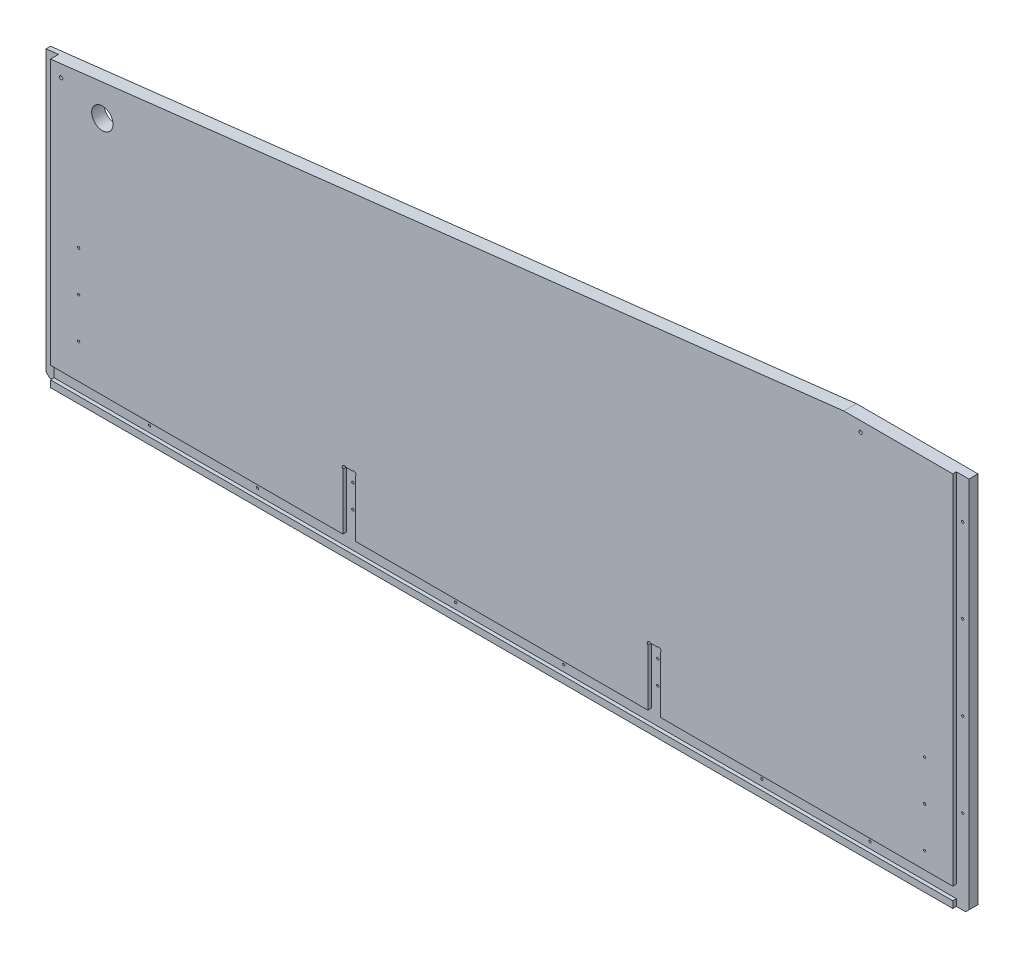
SolidWorks part; units mm, degrees
material "Pine"
ref_plane "Front Plane" through (0, 0, 0) normal (0, 0, 1) x (1, 0, 0)
ref_plane "Top Plane" through (0, 0, 0) normal (0, 1, 0) x (1, 0, 0)
ref_plane "Right Plane" through (0, 0, 0) normal (1, 0, 0) x (0, 0, -1)
sketch "Sketch1" plane through (0, 0, 0) normal (0, 0, 1) x (1, 0, 0)
  line L0 (8932.6508, -5243.5125) -> (10226.1458, -5243.5125)
  line L1 (9086.3208, -4722.0918) -> (10222.9708, -4853.7812)
  line L2 (8914.8708, -6342.0625) -> (10197.5708, -6342.0625)
  line L3 (8914.8708, -5808.6625) -> (10197.5708, -5808.6625)
  line L4 (8919.6333, -5253.0375) -> (10218.2083, -5253.0375)
  line L5 (9134.2633, -4656.1375) -> (9134.2633, -4638.3575)
  line L6 (9091.0833, -4638.3575) -> (9134.2633, -4638.3575)
  line L7 (9091.0833, -4567.2375) -> (9091.0833, -4638.3575)
  line L8 (9134.2633, -4656.1375) -> (9581.3033, -4656.1375)
  line L9 (9091.0833, -4567.2375) -> (9624.4833, -4567.2375)
  line L10 (9581.3033, -4656.1375) -> (9581.3033, -4638.3575)
  line L11 (9581.3033, -4638.3575) -> (9624.4833, -4638.3575)
  line L12 (9624.4833, -4567.2375) -> (9624.4833, -4638.3575)
  line L13 (8932.6508, -5225.7325) -> (9344.9775, -5225.7325)
  line L14 (8932.6508, -5256.2125) -> (8932.6508, -5243.5125)
  line L15 (8911.6958, -5256.2125) -> (8932.6508, -5256.2125)
  line L16 (8914.8708, -4722.0918) -> (9086.3208, -4722.0918)
  line L17 (8911.6958, -4715.5913) -> (8932.6508, -4715.5913)
  line L18 (8914.8708, -6342.0625) -> (8914.8708, -5808.6625)
  line L19 (12082.9917, -4722.0918) -> (10946.3417, -4853.7812)
  line L20 (12236.6617, -5243.5125) -> (10943.1667, -5243.5125)
  line L21 (10951.1042, -5253.0375) -> (12249.6792, -5253.0375)
  line L22 (10838.3917, -5656.2625) -> (11308.2917, -5656.2625)
  line L23 (10838.3917, -5719.7625) -> (11308.2917, -5719.7625)
  line L24 (10838.3917, -5742.5368) -> (11308.2917, -5742.5368)
  line L25 (10806.6417, -6342.0625) -> (11340.0417, -6342.0625)
  line L26 (10803.4667, -6335.7125) -> (11343.2167, -6335.7125)
  line L27 (10803.4667, -6317.9325) -> (11343.2167, -6317.9325)
  line L28 (10943.1667, -5225.7325) -> (11376.4483, -5225.7325)
  line L29 (11506.7292, -4754.5625) -> (10806.6417, -4827.5875)
  line L30 (11506.7292, -4567.2375) -> (11506.7292, -4754.5625)
  line L31 (10806.6417, -4567.2375) -> (10806.6417, -4827.5875)
  line L32 (10806.6417, -4567.2375) -> (11506.7292, -4567.2375)
  line L33 (10235.6708, -6329.3625) -> (10245.1958, -6329.3625)
  line L34 (10245.1958, -6329.3625) -> (10254.7208, -6278.5625)
  line L35 (10302.3458, -6329.3625) -> (10311.8708, -6278.5625)
  line L36 (10302.3458, -6329.3625) -> (10292.8208, -6329.3625)
  line L37 (10245.1958, -5821.3625) -> (10254.7208, -5872.1625)
  line L38 (10235.6708, -5821.3625) -> (10245.1958, -5821.3625)
  line L39 (10292.8208, -5821.3625) -> (10302.3458, -5821.3625)
  line L40 (10302.3458, -5821.3625) -> (10311.8708, -5872.1625)
  line L41 (10235.6708, -5821.3625) -> (10235.6708, -6329.3625)
  line L42 (10254.7208, -5872.1625) -> (10254.7208, -6278.5625)
  line L43 (10311.8708, -5872.1625) -> (10311.8708, -6278.5625)
  line L44 (10292.8208, -5821.3625) -> (10292.8208, -6329.3625)
  line L45 (8932.6508, -5225.7325) -> (8932.6508, -4715.5913)
  line L46 (8911.6958, -4715.5913) -> (8911.6958, -5256.2125)
  line L47 (8914.8708, -5248.275) -> (8914.8708, -4722.0918)
  line L48 (8919.6333, -5253.0375) -> (8914.8708, -5248.275)
  line L49 (8914.8708, -5145.0875) -> (8937.426, -5145.0875)
  line L50 (8914.8708, -5202.2375) -> (8937.426, -5202.2375)
  line L51 (10838.3917, -5656.2625) -> (10838.3917, -5719.7625)
  line L52 (10832.0417, -5736.1868) -> (10856.1717, -5736.1868)
  line L53 (10806.6417, -6342.0625) -> (10806.6417, -5818.7368)
  line L54 (10832.0417, -5649.9125) -> (10856.1717, -5649.9125)
  line L55 (10832.0417, -5726.1125) -> (10856.1717, -5726.1125)
  line L56 (10806.6417, -5818.7368) -> (10833.9015, -5818.7368)
  line L57 (10832.0417, -5806.0442) -> (10851.6815, -5806.0442)
  line L58 (10856.1717, -5801.5541) -> (10856.1717, -5736.1868)
  line L59 (10838.3917, -5814.2467) -> (10838.3917, -5742.5368)
  line L60 (10832.0417, -5806.0442) -> (10832.0417, -5736.1868)
  line L61 (10803.4667, -6317.9325) -> (10803.4667, -6335.7125)
  line L62 (10197.5708, -5808.6625) -> (10197.5708, -6342.0625)
  line L63 (9762.3842, -6348.4125) -> (9762.3842, -5802.3125)
  line L64 (9780.1642, -6348.4125) -> (9762.3842, -6348.4125)
  line L65 (9780.1642, -5802.3125) -> (9780.1642, -6348.4125)
  line L66 (9762.3842, -5802.3125) -> (9780.1642, -5802.3125)
  line L67 (9332.2775, -6348.4125) -> (9332.2775, -5802.3125)
  line L68 (9332.2775, -6348.4125) -> (9350.0575, -6348.4125)
  line L69 (9350.0575, -5802.3125) -> (9350.0575, -6348.4125)
  line L70 (9332.2775, -5802.3125) -> (9350.0575, -5802.3125)
  line L71 (9993.8374, -6061.075) -> (9993.8374, -6045.2418)
  line L72 (9998.5999, -6065.8375) -> (10014.4331, -6065.8375)
  line L73 (9998.5999, -6084.8875) -> (10014.4331, -6084.8875)
  line L74 (9993.8374, -6105.4832) -> (9993.8374, -6089.65)
  line L75 (9974.7874, -6105.4832) -> (9974.7874, -6089.65)
  line L76 (9954.1917, -6084.8875) -> (9970.0249, -6084.8875)
  line L77 (9974.7874, -6061.075) -> (9974.7874, -6045.2418)
  line L78 (9954.1917, -6065.8375) -> (9970.0249, -6065.8375)
  line L79 (10793.9417, -6237.2875) -> (10816.4969, -6237.2875)
  line L80 (10793.9417, -6294.4375) -> (10816.4969, -6294.4375)
  line L81 (10856.1717, -5649.9125) -> (10856.1717, -5726.1125)
  line L82 (10832.0417, -5726.1125) -> (10832.0417, -5649.9125)
  line L83 (10226.1458, -5225.7325) -> (10226.1458, -5243.5125)
  line L84 (10205.1908, -5257.8) -> (10205.1908, -4844.2499)
  line L85 (10230.9083, -4844.2499) -> (10230.9083, -5257.8)
  line L86 (10205.1908, -5257.8) -> (10230.9083, -5257.8)
  line L87 (10205.1908, -4844.2499) -> (10230.9083, -4844.2499)
  line L88 (10946.3417, -5176.8375) -> (10968.8969, -5176.8375)
  line L89 (9349.4676, -5141.9125) -> (9358.2674, -5141.9125)
  line L90 (10946.3417, -5119.6875) -> (10968.8969, -5119.6875)
  line L91 (9929.011, -4660.9635) -> (10066.0807, -4660.9635)
  line L92 (9929.011, -4678.7435) -> (10066.0807, -4678.7435)
  line L93 (10943.1667, -5225.7325) -> (10943.1667, -5243.5125)
  line L94 (10946.3417, -5248.275) -> (10951.1042, -5253.0375)
  line L95 (10946.3417, -5257.8063) -> (10946.3417, -4849.0188)
  line L96 (10964.1217, -5257.8) -> (10964.1217, -4844.2499)
  line L97 (10938.4042, -4844.2499) -> (10938.4042, -5257.8)
  line L98 (10938.4042, -5257.8) -> (10964.1217, -5257.8)
  line L99 (10964.1217, -4844.2499) -> (10938.4042, -4844.2499)
  line L100 (10344.8908, -4560.8875) -> (10369.0208, -4560.8875)
  line L101 (10344.8908, -4560.8875) -> (10369.0208, -4560.8875)
  line L102 (10800.2917, -4560.8875) -> (10824.4217, -4560.8875)
  line L103 (10200.4156, -5119.6875) -> (10222.9708, -5119.6875)
  line L104 (10200.4156, -5176.8375) -> (10222.9708, -5176.8375)
  line L105 (9344.9775, -5146.4026) -> (9344.9775, -5225.7325)
  line L106 (10344.8908, -4560.8875) -> (10344.8908, -4833.9375)
  line L107 (9792.8642, -5225.7325) -> (9792.8642, -5146.4026)
  line L108 (9362.7575, -5225.7325) -> (9775.0842, -5225.7325)
  line L109 (9680.3633, -4761.8396) -> (9680.3633, -4559.9604)
  line L110 (9656.2333, -4559.9604) -> (9680.3633, -4559.9604)
  line L111 (9656.2333, -4761.8396) -> (9680.3633, -4761.8396)
  line L112 (9656.2333, -4761.8396) -> (9656.2333, -4559.9604)
  line L113 (9779.5743, -5141.9125) -> (9788.374, -5141.9125)
  line L114 (10070.5708, -4665.4536) -> (10070.5708, -4674.2534)
  line L115 (9924.5208, -4674.2534) -> (9924.5208, -4665.4536)
  line L116 (12127.4417, -6188.3925) -> (12205.5015, -6188.3925)
  line L117 (12209.9917, -6170.6125) -> (12209.9917, -6183.9024)
  line L118 (9792.8642, -5225.7325) -> (10226.1458, -5225.7325)
  line L119 (9662.5833, -4754.5625) -> (10362.6708, -4827.5875)
  line L120 (9662.5833, -4567.2375) -> (9662.5833, -4754.5625)
  line L121 (10362.6708, -4567.2375) -> (10362.6708, -4827.5875)
  line L122 (9662.5833, -4567.2375) -> (10362.6708, -4567.2375)
  line L123 (10824.4217, -4833.9375) -> (10800.2917, -4833.9375)
  line L124 (10800.2917, -4833.9375) -> (10800.2917, -4560.8875)
  line L125 (10824.4217, -4560.8875) -> (10824.4217, -4833.9375)
  line L126 (10344.8908, -4833.9375) -> (10369.0208, -4833.9375)
  line L127 (10369.0208, -4833.9375) -> (10369.0208, -4560.8875)
  line L128 (10222.9708, -5248.275) -> (10218.2083, -5253.0375)
  line L129 (10222.9708, -5257.8063) -> (10222.9708, -4849.0188)
  line L130 (11734.6544, -5701.375) -> (11739.2301, -5701.375)
  line L131 (9362.7575, -5225.7325) -> (9362.7575, -5146.4026)
  line L132 (9775.0842, -5146.4026) -> (9775.0842, -5225.7325)
  line L133 (11761.3864, -5701.375) -> (11756.8282, -5701.375)
  line L134 (11734.6544, -5693.755) -> (11739.2301, -5693.755)
  line L135 (11761.4039, -5693.755) -> (11756.8282, -5693.755)
  line L136 (11734.6544, -5701.375) -> (11739.2301, -5701.375)
  line L137 (11744.3462, -5721.3024) -> (11744.3462, -5706.4179)
  line L138 (11751.7122, -5721.3024) -> (11751.7122, -5706.4179)
  line L139 (11740.0917, -6170.6125) -> (11740.0917, -6183.9024)
  line L140 (11689.2917, -6188.3925) -> (11822.6417, -6188.3925)
  line L141 (11689.2917, -6348.4093) -> (11689.2917, -6164.2657)
  line L142 (11689.2917, -6164.2657) -> (11746.4417, -6164.2657)
  line L143 (11746.4417, -6164.2657) -> (11746.4417, -6188.3925)
  line L144 (11689.2917, -6164.2657) -> (11746.4417, -6164.2657)
  line L145 (11340.0417, -5818.7368) -> (11340.0417, -6342.0625)
  line L146 (11290.5117, -5726.1125) -> (11314.6417, -5726.1125)
  line L147 (11290.5117, -5649.9125) -> (11290.5117, -5726.1125)
  line L148 (11340.0417, -5818.7368) -> (11312.7818, -5818.7368)
  line L149 (11314.6417, -5806.0442) -> (11295.0018, -5806.0442)
  line L150 (11290.5117, -5801.5541) -> (11290.5117, -5736.1868)
  line L151 (11308.2917, -5814.2467) -> (11308.2917, -5742.5368)
  line L152 (11314.6417, -5806.0442) -> (11314.6417, -5736.1868)
  line L153 (11290.5117, -5736.1868) -> (11314.6417, -5736.1868)
  line L154 (11848.0417, -6267.1325) -> (11962.3417, -6267.1325)
  line L155 (11962.3417, -6267.1325) -> (11962.3417, -6203.6325)
  line L156 (11343.2167, -6317.9325) -> (11343.2167, -6335.7125)
  line L157 (11365.4417, -5656.2625) -> (11365.4417, -5719.7625)
  line L158 (11365.4417, -5656.2625) -> (11479.7417, -5656.2625)
  line L159 (11778.1917, -6071.3937) -> (11802.3217, -6071.3937)
  line L160 (11314.6417, -5726.1125) -> (11314.6417, -5649.9125)
  line L161 (11314.6417, -5649.9125) -> (11290.5117, -5649.9125)
  line L162 (11308.2917, -5719.7625) -> (11308.2917, -5656.2625)
  line L163 (11689.2917, -6348.4093) -> (11713.4217, -6348.4093)
  line L164 (12203.6417, -6164.2657) -> (12260.7917, -6164.2657)
  line L165 (11713.4217, -6348.4093) -> (11713.4217, -6164.2657)
  line L166 (11695.6417, -6342.0625) -> (11695.6417, -6170.6125)
  line L167 (11695.6417, -6048.5337) -> (11699.4517, -6052.3437)
  line L168 (11822.6417, -6292.5325) -> (11822.6417, -6188.3925)
  line L169 (11695.6417, -6342.0625) -> (11695.6417, -6170.6125)
  line L170 (11848.0417, -6203.6325) -> (11962.3417, -6203.6325)
  line L171 (11848.0417, -6203.6325) -> (11848.0417, -6267.1325)
  line L172 (11987.7417, -6267.1325) -> (11987.7417, -6203.6325)
  line L173 (11784.5417, -6077.7437) -> (11784.5417, -6141.2438)
  line L174 (11517.8417, -5656.2625) -> (11632.1417, -5656.2625)
  line L175 (11632.1417, -5656.2625) -> (11632.1417, -5719.7625)
  line L176 (11632.1417, -5719.7625) -> (11517.8417, -5719.7625)
  line L177 (11517.8417, -5719.7625) -> (11517.8417, -5656.2625)
  line L178 (11692.4667, -6028.2137) -> (11692.4667, -6045.9937)
  line L179 (11695.6417, -5979.3188) -> (11718.1969, -5979.3188)
  line L180 (11695.6417, -5922.1687) -> (11718.1969, -5922.1687)
  line L181 (11821.0415, -5722.9375) -> (11821.0415, -5943.6)
  line L182 (11687.7042, -5651.5) -> (11701.9917, -5651.5)
  line L183 (11687.7042, -5651.5) -> (11687.7042, -6055.5251)
  line L184 (11687.7042, -6055.5251) -> (11701.9917, -6055.5251)
  line L185 (11701.9917, -6055.5251) -> (11701.9917, -5651.5)
  line L186 (11695.6417, -6055.2013) -> (11695.6417, -5649.595)
  line L187 (11695.6417, -5656.2625) -> (11695.6417, -6048.5337)
  line L188 (11695.6417, -6170.6125) -> (11740.0917, -6170.6125)
  line L189 (12203.6417, -6164.2657) -> (12203.6417, -6188.3925)
  line L190 (12254.4417, -6342.0625) -> (12254.4417, -6170.6125)
  line L191 (12129.0419, -5943.6) -> (12129.0419, -5722.9375)
  line L192 (12254.4417, -6048.5337) -> (12250.6317, -6052.3437)
  line L193 (12257.6167, -6045.9937) -> (12257.6167, -6028.2137)
  line L194 (12248.0917, -5651.5) -> (12262.3792, -5651.5)
  line L195 (12262.3792, -5651.5) -> (12262.3792, -6055.5251)
  line L196 (12262.3792, -6055.5251) -> (12248.0917, -6055.5251)
  line L197 (12248.0917, -6055.5251) -> (12248.0917, -5651.5)
  line L198 (12254.4417, -6141.2438) -> (12254.4417, -6077.7437)
  line L199 (12236.6617, -6164.2657) -> (12260.7917, -6164.2657)
  line L200 (12102.0417, -6267.1325) -> (11987.7417, -6267.1325)
  line L201 (11330.1865, -6237.2875) -> (11352.7417, -6237.2875)
  line L202 (11330.1865, -6294.4375) -> (11352.7417, -6294.4375)
  line L203 (11474.6617, -5851.8425) -> (11492.4417, -5851.8425)
  line L204 (11474.6617, -5808.6625) -> (11474.6617, -5851.8425)
  line L205 (11403.5417, -5808.6625) -> (11474.6617, -5808.6625)
  line L206 (11492.4417, -5851.8425) -> (11492.4417, -6298.8825)
  line L207 (11403.5417, -6342.0625) -> (11403.5417, -5808.6625)
  line L208 (11474.6617, -6298.8825) -> (11492.4417, -6298.8825)
  line L209 (11474.6617, -6342.0625) -> (11474.6617, -6298.8825)
  line L210 (11403.5417, -6342.0625) -> (11474.6617, -6342.0625)
  line L211 (11619.4417, -5851.8425) -> (11601.6617, -5851.8425)
  line L212 (11601.6617, -5808.6625) -> (11601.6617, -5851.8425)
  line L213 (11530.5417, -5808.6625) -> (11601.6617, -5808.6625)
  line L214 (11619.4417, -5851.8425) -> (11619.4417, -6298.8825)
  line L215 (11530.5417, -6342.0625) -> (11530.5417, -5808.6625)
  line L216 (11619.4417, -6298.8825) -> (11601.6617, -6298.8825)
  line L217 (11601.6617, -6342.0625) -> (11601.6617, -6298.8825)
  line L218 (11530.5417, -6342.0625) -> (11601.6617, -6342.0625)
  line L219 (11479.7417, -5719.7625) -> (11479.7417, -5656.2625)
  line L220 (11365.4417, -5719.7625) -> (11479.7417, -5719.7625)
  line L221 (11778.1917, -6147.5937) -> (11802.3217, -6147.5937)
  line L222 (11802.3217, -6071.3937) -> (11802.3217, -6147.5937)
  line L223 (11778.1917, -6147.5937) -> (11778.1917, -6071.3937)
  line L224 (12254.4417, -5922.1687) -> (12231.8865, -5922.1687)
  line L225 (12254.4417, -5979.3188) -> (12231.8865, -5979.3188)
  line L226 (12254.4417, -6055.2013) -> (12254.4417, -5649.595)
  line L227 (12254.4417, -6048.5337) -> (12254.4417, -5656.2625)
  line L228 (11841.6917, -5702.2873) -> (12108.3917, -5702.2873)
  line L229 (11822.6417, -6292.5325) -> (12127.4417, -6292.5325)
  line L230 (12127.4417, -6292.5325) -> (12127.4417, -6188.3925)
  line L231 (12254.4417, -6170.6125) -> (12209.9917, -6170.6125)
  line L232 (11695.6417, -6342.0625) -> (12254.4417, -6342.0625)
  line L233 (12236.6617, -6348.4093) -> (12260.7917, -6348.4093)
  line L234 (12260.7917, -6348.4093) -> (12260.7917, -6164.2657)
  line L235 (12236.6617, -6348.4093) -> (12236.6617, -6164.2657)
  line L236 (12102.0417, -6203.6325) -> (12102.0417, -6267.1325)
  line L237 (11987.7417, -6203.6325) -> (12102.0417, -6203.6325)
  line L238 (12236.6617, -6147.5937) -> (12236.6617, -6071.3937)
  line L239 (12203.6417, -6188.3925) -> (12260.7917, -6188.3925)
  line L240 (11098.7417, -4665.4536) -> (11098.7417, -4674.2534)
  line L241 (11394.2283, -5146.4026) -> (11394.2283, -5225.7325)
  line L242 (11376.4483, -5225.7325) -> (11376.4483, -5146.4026)
  line L243 (11394.2283, -5225.7325) -> (11806.555, -5225.7325)
  line L244 (11841.6917, -5964.2502) -> (12108.3917, -5964.2502)
  line L245 (12236.6617, -6147.5937) -> (12260.7917, -6147.5937)
  line L246 (12236.6617, -5256.2125) -> (12236.6617, -5243.5125)
  line L247 (12260.7917, -6147.5937) -> (12260.7917, -6071.3937)
  line L248 (12260.7917, -6071.3937) -> (12236.6617, -6071.3937)
  line L249 (12254.4417, -6077.7437) -> (11784.5417, -6077.7437)
  line L250 (11784.5417, -6141.2438) -> (12254.4417, -6141.2438)
  line L252 (12254.4417, -5656.2625) -> (11695.6417, -5656.2625)
  line L253 (11699.4517, -6052.3437) -> (12250.6317, -6052.3437)
  line L254 (11692.4667, -6045.9937) -> (12257.6167, -6045.9937)
  line L255 (11692.4667, -6028.2137) -> (12257.6167, -6028.2137)
  line L256 (11824.335, -5146.4026) -> (11824.335, -5225.7325)
  line L257 (11811.0451, -5141.9125) -> (11819.8449, -5141.9125)
  line L258 (11244.7917, -4674.2534) -> (11244.7917, -4665.4536)
  line L259 (11806.555, -5225.7325) -> (11806.555, -5146.4026)
  line L260 (11488.9492, -4761.8396) -> (11488.9492, -4559.9604)
  line L261 (11488.9492, -4559.9604) -> (11513.0792, -4559.9604)
  line L262 (11488.9492, -4761.8396) -> (11513.0792, -4761.8396)
  line L263 (11513.0792, -4761.8396) -> (11513.0792, -4559.9604)
  line L264 (11240.3015, -4660.9635) -> (11103.2318, -4660.9635)
  line L265 (11103.2318, -4678.7435) -> (11240.3015, -4678.7435)
  line L266 (12236.6617, -5225.7325) -> (12236.6617, -4715.5913)
  line L267 (12257.6167, -4715.5913) -> (12257.6167, -5256.2125)
  line L268 (12254.4417, -5248.275) -> (12254.4417, -4722.0918)
  line L269 (12236.6617, -5225.7325) -> (11824.335, -5225.7325)
  line L270 (12035.0492, -4656.1375) -> (12035.0492, -4638.3575)
  line L271 (12078.2292, -4638.3575) -> (12035.0492, -4638.3575)
  line L272 (12078.2292, -4567.2375) -> (12078.2292, -4638.3575)
  line L273 (12035.0492, -4656.1375) -> (11588.0092, -4656.1375)
  line L274 (11544.8292, -4567.2375) -> (12078.2292, -4567.2375)
  line L275 (11588.0092, -4656.1375) -> (11588.0092, -4638.3575)
  line L276 (11544.8292, -4638.3575) -> (11588.0092, -4638.3575)
  line L277 (11544.8292, -4567.2375) -> (11544.8292, -4638.3575)
  line L278 (12249.6792, -5253.0375) -> (12254.4417, -5248.275)
  line L280 (12257.6167, -5256.2125) -> (12236.6617, -5256.2125)
  line L281 (12231.8865, -5145.0875) -> (12254.4417, -5145.0875)
  line L282 (12231.8865, -5202.2375) -> (12254.4417, -5202.2375)
  line L283 (12236.6617, -4715.5913) -> (12257.6167, -4715.5913)
  line L284 (12082.9917, -4722.0918) -> (12254.4417, -4722.0918)
  line L285 (11380.9385, -5141.9125) -> (11389.7382, -5141.9125)
  circle A0 centre (8923.7608, -4778.9042) radius 1.5875
  circle A1 centre (9062.6598, -4736.3765) radius 2.3685
  circle A2 centre (9051.3958, -6281.7375) radius 22.225
  circle A3 centre (9083.1458, -6249.9875) radius 1.5875
  circle A4 centre (9083.1458, -6313.4875) radius 1.5875
  circle A5 centre (9019.6458, -6249.9875) radius 1.5875
  circle A6 centre (9019.6458, -6313.4875) radius 1.5875
  circle A7 centre (8972.3383, -5202.2375) radius 1.5875
  circle A8 centre (8923.7608, -5015.9708) radius 1.5875
  circle A9 centre (8923.7608, -5134.5042) radius 1.5875
  circle A10 centre (9054.5708, -5234.6225) radius 1.5875
  circle A11 centre (8923.7608, -4897.4375) radius 1.5875
  circle A12 centre (8972.3383, -5087.9375) radius 1.5875
  circle A13 centre (8972.3383, -5145.0875) radius 1.5875
  circle A14 centre (10847.2817, -5668.9625) radius 1.5875
  circle A15 centre (10847.2817, -5707.0625) radius 1.5875
  circle A16 centre (10847.2817, -5755.2368) radius 1.5875
  circle A17 centre (10851.4092, -6237.2875) radius 1.5875
  circle A18 centre (10851.4092, -6294.4375) radius 1.5875
  circle A19 centre (10847.2817, -5793.3442) radius 1.5875
  arc A20 (10833.9015, -5818.7368) -> (10838.3917, -5814.2467) centre (10836.1466, -5816.4918) ccw
  arc A21 (10851.6815, -5806.0442) -> (10856.1717, -5801.5541) centre (10853.9266, -5803.7992) ccw
  circle A22 centre (10882.8417, -6040.4375) radius 1.5875
  circle A23 centre (10882.8417, -6218.2375) radius 1.5875
  circle A24 centre (10882.8417, -5862.6375) radius 1.5875
  circle A25 centre (10908.2417, -6326.8225) radius 1.5875
  circle A26 centre (10908.2417, -6326.8225) radius 1.5875
  circle A27 centre (10851.4092, -6180.1375) radius 1.5875
  circle A28 centre (10815.5317, -4783.4231) radius 1.5875
  circle A29 centre (10815.5317, -4696.9488) radius 1.5875
  circle A30 centre (10815.5317, -4610.4746) radius 1.5875
  circle A31 centre (10979.1323, -4867.0082) radius 2.3685
  circle A32 centre (10190.1802, -4867.0082) radius 2.3685
  circle A33 centre (10955.2317, -4929.9812) radius 1.5875
  circle A34 centre (10955.2317, -5031.5812) radius 1.5875
  circle A35 centre (10214.0808, -4929.9812) radius 1.5875
  circle A36 centre (10214.0808, -5031.5812) radius 1.5875
  circle A37 centre (9341.1675, -6265.8625) radius 1.5875
  circle A38 centre (9771.2742, -5884.8625) radius 1.5875
  circle A39 centre (9771.2742, -6138.8625) radius 1.5875
  circle A40 centre (9771.2742, -6011.8625) radius 1.5875
  arc A41 (10036.2287, -6113.8083) -> (10051.3426, -6111.6033) centre (10042.9639, -6107.0732) ccw
  arc A42 (10051.3426, -6111.6033) -> (10051.3426, -6039.1217) centre (9984.3124, -6075.3625) ccw
  arc A43 (10051.3426, -6039.1217) -> (10036.2287, -6036.9167) centre (10042.9639, -6043.6518) ccw
  arc A44 (10034.5851, -6102.5431) -> (10034.5851, -6048.1819) centre (9984.3124, -6075.3625) ccw
  arc A45 (10034.5851, -6102.5431) -> (10036.2287, -6113.8083) centre (10042.9639, -6107.0732) ccw
  arc A46 (10036.2287, -6036.9167) -> (10034.5851, -6048.1819) centre (10042.9639, -6043.6518) ccw
  arc A47 (9945.8666, -6127.2787) -> (9948.0717, -6142.3927) centre (9952.6018, -6134.0139) ccw
  arc A48 (9948.0717, -6142.3927) -> (10020.5532, -6142.3927) centre (9984.3124, -6075.3625) ccw
  arc A49 (10020.5532, -6142.3927) -> (10022.7583, -6127.2787) centre (10016.0231, -6134.0139) ccw
  arc A50 (9957.1319, -6125.6352) -> (10011.493, -6125.6352) centre (9984.3124, -6075.3625) ccw
  arc A51 (9957.1319, -6125.6352) -> (9945.8666, -6127.2787) centre (9952.6018, -6134.0139) ccw
  arc A52 (10022.7583, -6127.2787) -> (10011.493, -6125.6352) centre (10016.0231, -6134.0139) ccw
  arc A53 (9932.3962, -6036.9167) -> (9917.2822, -6039.1217) centre (9925.661, -6043.6518) ccw
  arc A54 (9917.2822, -6039.1217) -> (9917.2822, -6111.6033) centre (9984.3124, -6075.3625) ccw
  arc A55 (9917.2822, -6111.6033) -> (9932.3962, -6113.8083) centre (9925.661, -6107.0732) ccw
  arc A56 (9934.0398, -6048.1819) -> (9934.0398, -6102.5431) centre (9984.3124, -6075.3625) ccw
  arc A57 (9934.0398, -6048.1819) -> (9932.3962, -6036.9167) centre (9925.661, -6043.6518) ccw
  arc A58 (9932.3962, -6113.8083) -> (9934.0398, -6102.5431) centre (9925.661, -6107.0732) ccw
  arc A59 (9945.8666, -6023.4463) -> (9957.1319, -6025.0898) centre (9952.6018, -6016.7111) ccw
  arc A60 (10011.493, -6025.0898) -> (10022.7583, -6023.4463) centre (10016.0231, -6016.7111) ccw
  arc A61 (10011.493, -6025.0898) -> (9957.1319, -6025.0898) centre (9984.3124, -6075.3625) ccw
  arc A62 (9948.0717, -6008.3323) -> (9945.8666, -6023.4463) centre (9952.6018, -6016.7111) ccw
  arc A63 (10020.5532, -6008.3323) -> (9948.0717, -6008.3323) centre (9984.3124, -6075.3625) ccw
  arc A64 (10022.7583, -6023.4463) -> (10020.5532, -6008.3323) centre (10016.0231, -6016.7111) ccw
  arc A65 (10005.0943, -6187.7574) -> (10096.7073, -6096.1443) centre (9984.3124, -6075.3625) ccw
  arc A66 (9993.8374, -6178.3911) -> (10005.0943, -6187.7574) centre (10003.3624, -6178.3911) ccw
  arc A67 (10001.6306, -6169.0249) -> (10077.9748, -6092.6807) centre (9984.3124, -6075.3625) ccw
  arc A68 (10087.3411, -6084.8875) -> (10077.9748, -6092.6807) centre (10087.3411, -6094.4125) ccw
  arc A69 (10001.6306, -6169.0249) -> (9993.8374, -6178.3911) centre (10003.3624, -6178.3911) ccw
  arc A70 (9963.5306, -6187.7574) -> (9974.7874, -6178.3911) centre (9965.2624, -6178.3911) ccw
  arc A71 (9871.9176, -6096.1443) -> (9963.5306, -6187.7574) centre (9984.3124, -6075.3625) ccw
  arc A72 (9881.2838, -6084.8875) -> (9871.9176, -6096.1443) centre (9881.2838, -6094.4125) ccw
  arc A73 (9890.65, -6092.6807) -> (9966.9943, -6169.0249) centre (9984.3124, -6075.3625) ccw
  arc A74 (9974.7874, -6178.3911) -> (9966.9943, -6169.0249) centre (9965.2624, -6178.3911) ccw
  arc A75 (9890.65, -6092.6807) -> (9881.2838, -6084.8875) centre (9881.2838, -6094.4125) ccw
  arc A76 (9871.9176, -6054.5807) -> (9881.2838, -6065.8375) centre (9881.2838, -6056.3125) ccw
  arc A77 (9963.5306, -5962.9676) -> (9871.9176, -6054.5807) centre (9984.3124, -6075.3625) ccw
  arc A78 (9974.7874, -5972.3339) -> (9963.5306, -5962.9676) centre (9965.2624, -5972.3339) ccw
  arc A79 (9966.9943, -5981.7001) -> (9890.65, -6058.0443) centre (9984.3124, -6075.3625) ccw
  arc A80 (9881.2838, -6065.8375) -> (9890.65, -6058.0443) centre (9881.2838, -6056.3125) ccw
  arc A81 (9966.9943, -5981.7001) -> (9974.7874, -5972.3339) centre (9965.2624, -5972.3339) ccw
  arc A82 (10077.9748, -6058.0443) -> (10087.3411, -6065.8375) centre (10087.3411, -6056.3125) ccw
  arc A83 (9993.8374, -5972.3339) -> (10001.6306, -5981.7001) centre (10003.3624, -5972.3339) ccw
  arc A84 (10077.9748, -6058.0443) -> (10001.6306, -5981.7001) centre (9984.3124, -6075.3625) ccw
  arc A85 (10087.3411, -6065.8375) -> (10096.7073, -6054.5807) centre (10087.3411, -6056.3125) ccw
  arc A86 (10096.7073, -6054.5807) -> (10005.0943, -5962.9676) centre (9984.3124, -6075.3625) ccw
  arc A87 (10005.0943, -5962.9676) -> (9993.8374, -5972.3339) centre (10003.3624, -5972.3339) ccw
  arc A88 (10014.4331, -6065.8375) -> (10018.7361, -6059.0339) centre (10014.4331, -6061.075) ccw
  arc A89 (10018.7361, -6059.0339) -> (10000.641, -6040.9388) centre (9984.3124, -6075.3625) ccw
  arc A90 (10000.641, -6040.9388) -> (9993.8374, -6045.2418) centre (9998.5999, -6045.2418) ccw
  arc A91 (9993.8374, -6061.075) -> (9998.5999, -6065.8375) centre (9998.5999, -6061.075) ccw
  arc A92 (9993.8374, -6105.4832) -> (10000.641, -6109.7862) centre (9998.5999, -6105.4832) ccw
  arc A93 (10000.641, -6109.7862) -> (10018.7361, -6091.6911) centre (9984.3124, -6075.3625) ccw
  arc A94 (10018.7361, -6091.6911) -> (10014.4331, -6084.8875) centre (10014.4331, -6089.65) ccw
  arc A95 (9998.5999, -6084.8875) -> (9993.8374, -6089.65) centre (9998.5999, -6089.65) ccw
  arc A96 (9954.1917, -6084.8875) -> (9949.8888, -6091.6911) centre (9954.1917, -6089.65) ccw
  arc A97 (9949.8888, -6091.6911) -> (9967.9839, -6109.7862) centre (9984.3124, -6075.3625) ccw
  arc A98 (9967.9839, -6109.7862) -> (9974.7874, -6105.4832) centre (9970.0249, -6105.4832) ccw
  arc A99 (9974.7874, -6089.65) -> (9970.0249, -6084.8875) centre (9970.0249, -6089.65) ccw
  arc A100 (9970.0249, -6065.8375) -> (9974.7874, -6061.075) centre (9970.0249, -6061.075) ccw
  arc A101 (9949.8888, -6059.0339) -> (9954.1917, -6065.8375) centre (9954.1917, -6061.075) ccw
  arc A102 (9967.9839, -6040.9388) -> (9949.8888, -6059.0339) centre (9984.3124, -6075.3625) ccw
  arc A103 (9974.7874, -6045.2418) -> (9967.9839, -6040.9388) centre (9970.0249, -6045.2418) ccw
  arc A104 (10096.7073, -6096.1443) -> (10087.3411, -6084.8875) centre (10087.3411, -6094.4125) ccw
  circle A105 centre (9771.2742, -6265.8625) radius 1.5875
  circle A106 centre (9341.1675, -5884.8625) radius 1.5875
  circle A107 centre (9341.1675, -6138.8625) radius 1.5875
  circle A108 centre (9341.1675, -6011.8625) radius 1.5875
  circle A109 centre (11037.2315, -4887.5494) radius 15.0812
  arc A110 (9349.4676, -5141.9125) -> (9344.9775, -5146.4026) centre (9347.2226, -5144.1576) ccw
  arc A111 (9362.7575, -5146.4026) -> (9358.2674, -5141.9125) centre (9360.5124, -5144.1576) ccw
  circle A112 centre (9946.7458, -4669.8535) radius 1.5875
  arc A113 (9924.5208, -4674.2534) -> (9929.011, -4678.7435) centre (9926.7659, -4676.4984) ccw
  circle A114 centre (11003.8092, -5176.8375) radius 1.5875
  circle A115 centre (11003.8092, -5119.6875) radius 1.5875
  circle A116 centre (10353.7808, -4696.9488) radius 1.5875
  circle A117 centre (10353.7808, -4610.4746) radius 1.5875
  circle A118 centre (10353.7808, -4783.4231) radius 1.5875
  circle A119 centre (11003.8092, -5062.5375) radius 1.5875
  circle A120 centre (9353.8675, -5160.9625) radius 1.5875
  circle A121 centre (9638.7708, -5234.6225) radius 1.5875
  circle A122 centre (9671.4733, -4724.1144) radius 1.5875
  circle A123 centre (9671.4733, -4661.3637) radius 1.5875
  circle A124 centre (9671.4733, -4598.6129) radius 1.5875
  arc A125 (9792.8642, -5146.4026) -> (9788.374, -5141.9125) centre (9790.6191, -5144.1576) ccw
  arc A126 (9779.5743, -5141.9125) -> (9775.0842, -5146.4026) centre (9777.3292, -5144.1576) ccw
  circle A127 centre (10048.3458, -4669.8535) radius 1.5875
  arc A128 (10070.5708, -4665.4536) -> (10066.0807, -4660.9635) centre (10068.3258, -4663.2086) ccw
  arc A129 (10066.0807, -4678.7435) -> (10070.5708, -4674.2534) centre (10068.3258, -4676.4984) ccw
  circle A130 centre (9997.5458, -4669.8535) radius 1.5875
  arc A131 (9929.011, -4660.9635) -> (9924.5208, -4665.4536) centre (9926.7659, -4663.2086) ccw
  circle A132 centre (10132.081, -4887.5494) radius 15.0812
  circle A133 centre (10165.5033, -5176.8375) radius 1.5875
  circle A134 centre (10165.5033, -5119.6875) radius 1.5875
  circle A135 centre (9486.3708, -5234.6225) radius 1.5875
  circle A136 centre (10165.5033, -5062.5375) radius 1.5875
  circle A137 centre (9206.9708, -5234.6225) radius 1.5875
  circle A138 centre (10070.5708, -5234.6225) radius 1.5875
  circle A139 centre (9918.1708, -5234.6225) radius 1.5875
  circle A140 centre (9783.9742, -5160.9625) radius 1.5875
  circle A141 centre (9783.9742, -5193.9825) radius 1.5875
  circle A142 centre (9353.8675, -5193.9825) radius 1.5875
  circle A143 centre (11073.3417, -6326.8225) radius 1.5875
  circle A144 centre (11073.3417, -6326.8225) radius 1.5875
  circle A145 centre (11295.2742, -6180.1375) radius 1.5875
  circle A146 centre (11295.2742, -6294.4375) radius 1.5875
  circle A147 centre (11295.2742, -6237.2875) radius 1.5875
  circle A148 centre (11975.0417, -5692.775) radius 3.4925
  circle A149 centre (11263.8417, -5862.6375) radius 1.5875
  arc A150 (11739.2301, -5701.375) -> (11744.3462, -5706.4179) centre (11748.0292, -5697.565) ccw
  arc A151 (11751.7122, -5706.4179) -> (11756.8282, -5701.375) centre (11748.0292, -5697.565) ccw
  arc A152 (11744.3462, -5721.3024) -> (11751.7122, -5721.3024) centre (11748.0292, -5725.505) ccw
  arc A153 (11734.6544, -5693.755) -> (11724.9787, -5697.565) centre (11730.5667, -5697.565) ccw
  arc A154 (11756.8282, -5693.755) -> (11739.2301, -5693.755) centre (11748.0292, -5697.565) ccw
  arc A155 (11724.9787, -5697.565) -> (11734.6544, -5701.375) centre (11730.5667, -5697.565) ccw
  arc A156 (11761.3864, -5701.375) -> (11771.0797, -5697.565) centre (11765.4842, -5697.565) ccw
  arc A157 (11771.0797, -5697.565) -> (11761.4039, -5693.755) centre (11765.4917, -5697.565) ccw
  arc A158 (11740.0917, -6183.9024) -> (11744.5818, -6188.3925) centre (11742.3367, -6186.1474) ccw
  arc A159 (12205.5015, -6188.3925) -> (12209.9917, -6183.9024) centre (12207.7466, -6186.1474) ccw
  circle A160 centre (11299.4017, -5793.3442) radius 1.5875
  arc A161 (11308.2917, -5814.2467) -> (11312.7818, -5818.7368) centre (11310.5367, -5816.4918) ccw
  arc A162 (11290.5117, -5801.5541) -> (11295.0018, -5806.0442) centre (11292.7567, -5803.7992) ccw
  circle A163 centre (11704.5317, -6314.149) radius 1.5875
  circle A164 centre (11748.9817, -6208.7125) radius 1.5875
  circle A165 centre (11263.8417, -6218.2375) radius 1.5875
  circle A166 centre (11263.8417, -6040.4375) radius 1.5875
  circle A167 centre (11238.4417, -6326.8225) radius 1.5875
  circle A168 centre (11238.4417, -6326.8225) radius 1.5875
  circle A169 centre (11299.4017, -5668.9625) radius 1.5875
  circle A170 centre (11299.4017, -5707.0625) radius 1.5875
  circle A171 centre (11726.7567, -6179.5025) radius 1.5875
  circle A172 centre (11704.5317, -6199.3198) radius 1.5875
  circle A173 centre (11748.9817, -6272.2125) radius 1.5875
  circle A174 centre (11704.5317, -6256.7344) radius 1.5875
  circle A175 centre (11299.4017, -5755.2368) radius 1.5875
  circle A176 centre (11913.4467, -6301.4225) radius 1.5875
  circle A177 centre (11790.2567, -6301.4225) radius 1.5875
  circle A178 centre (11793.4317, -6128.5437) radius 1.5875
  circle A179 centre (11753.1092, -5865.0188) radius 1.5875
  circle A180 centre (11809.9417, -6037.1038) radius 1.5875
  circle A181 centre (11809.9417, -6037.1038) radius 1.5875
  circle A182 centre (11753.1092, -5922.1687) radius 1.5875
  circle A183 centre (11975.0417, -5973.7625) radius 3.4925
  circle A184 centre (11975.0417, -6037.1038) radius 1.5875
  circle A185 centre (11753.1092, -5979.3188) radius 1.5875
  circle A186 centre (11975.0417, -6037.1038) radius 1.5875
  arc A187 (11841.6917, -5702.2873) -> (11821.0415, -5722.9375) centre (11841.6917, -5722.9375) ccw
  circle A188 centre (11811.5292, -5833.2687) radius 3.4925
  arc A189 (11821.0415, -5943.6) -> (11841.6917, -5964.2502) centre (11841.6917, -5943.6) ccw
  circle A190 centre (12196.9742, -5865.0188) radius 1.5875
  arc A191 (12129.0419, -5722.9375) -> (12108.3917, -5702.2873) centre (12108.3917, -5722.9375) ccw
  circle A192 centre (12036.6367, -6301.4225) radius 1.5875
  circle A193 centre (12159.8267, -6301.4225) radius 1.5875
  circle A194 centre (12138.5542, -5833.2687) radius 3.4925
  circle A195 centre (12197.2917, -5761.0375) radius 15.0812
  circle A196 centre (11793.4317, -6090.4437) radius 1.5875
  circle A197 centre (12196.9742, -5922.1687) radius 1.5875
  arc A198 (12108.3917, -5964.2502) -> (12129.0419, -5943.6) centre (12108.3917, -5943.6) ccw
  circle A199 centre (12196.9742, -5979.3188) radius 1.5875
  circle A200 centre (12201.1017, -6272.2125) radius 1.5875
  circle A201 centre (12245.5517, -6314.149) radius 1.5875
  circle A202 centre (12245.5517, -6256.7344) radius 1.5875
  circle A203 centre (12201.1017, -6208.7125) radius 1.5875
  circle A204 centre (12223.3267, -6179.5025) radius 1.5875
  circle A205 centre (12245.5517, -6199.3198) radius 1.5875
  circle A206 centre (11171.7667, -4669.8535) radius 1.5875
  circle A207 centre (11222.5667, -4669.8535) radius 1.5875
  arc A208 (11240.3015, -4678.7435) -> (11244.7917, -4674.2534) centre (11242.5466, -4676.4984) ccw
  circle A209 centre (11385.3383, -5193.9825) radius 1.5875
  circle A210 centre (12106.6527, -4736.3765) radius 2.3685
  circle A211 centre (12140.1417, -6037.1038) radius 1.5875
  circle A212 centre (12140.1417, -6037.1038) radius 1.5875
  circle A213 centre (12245.5517, -6090.4437) radius 1.5875
  circle A214 centre (12245.5517, -6128.5437) radius 1.5875
  circle A215 centre (11385.3383, -5160.9625) radius 1.5875
  arc A216 (11824.335, -5146.4026) -> (11819.8449, -5141.9125) centre (11822.0899, -5144.1576) ccw
  arc A217 (11811.0451, -5141.9125) -> (11806.555, -5146.4026) centre (11808.8001, -5144.1576) ccw
  circle A218 centre (11815.445, -5193.9825) radius 1.5875
  circle A219 centre (11815.445, -5160.9625) radius 1.5875
  circle A220 centre (11530.5417, -5234.6225) radius 1.5875
  circle A221 centre (11962.3417, -5234.6225) radius 1.5875
  arc A222 (11244.7917, -4665.4536) -> (11240.3015, -4660.9635) centre (11242.5466, -4663.2086) ccw
  circle A223 centre (11682.9417, -5234.6225) radius 1.5875
  circle A224 centre (11497.8392, -4724.1144) radius 1.5875
  circle A225 centre (11497.8392, -4661.3637) radius 1.5875
  circle A226 centre (11497.8392, -4598.6129) radius 1.5875
  circle A227 centre (11120.9667, -4669.8535) radius 1.5875
  arc A228 (11103.2318, -4660.9635) -> (11098.7417, -4665.4536) centre (11100.9867, -4663.2086) ccw
  arc A229 (11098.7417, -4674.2534) -> (11103.2318, -4678.7435) centre (11100.9867, -4676.4984) ccw
  circle A230 centre (12196.9742, -5202.2375) radius 1.5875
  circle A231 centre (12245.5517, -5015.9708) radius 1.5875
  circle A232 centre (12245.5517, -5134.5042) radius 1.5875
  circle A233 centre (12114.7417, -5234.6225) radius 1.5875
  circle A234 centre (12245.5517, -4897.4375) radius 1.5875
  circle A235 centre (12245.5517, -4778.9042) radius 1.5875
  circle A236 centre (12196.9742, -5087.9375) radius 1.5875
  circle A237 centre (12196.9742, -5145.0875) radius 1.5875
  circle A238 centre (11098.7417, -5234.6225) radius 1.5875
  circle A239 centre (11251.1417, -5234.6225) radius 1.5875
  arc A240 (11380.9385, -5141.9125) -> (11376.4483, -5146.4026) centre (11378.6934, -5144.1576) ccw
  arc A241 (11394.2283, -5146.4026) -> (11389.7382, -5141.9125) centre (11391.9833, -5144.1576) ccw
sketch "Sketch2" plane through (0, 0, 0) normal (0, 0, 1) x (1, 0, 0)
  line L0 (10946.3417, -4853.7812) -> (10946.3417, -5248.275)
  line L1 (10946.3417, -5248.275) -> (10951.1042, -5253.0375)
  line L2 (10951.1042, -5253.0375) -> (12249.6792, -5253.0375)
  line L3 (12249.6792, -5253.0375) -> (12254.4417, -5248.275)
  line L4 (12254.4417, -5248.275) -> (12254.4417, -4722.0918)
  line L5 (12254.4417, -4722.0918) -> (12082.9917, -4722.0918)
  line L6 (12082.9917, -4722.0918) -> (12254.4417, -4722.0918) construction
  line L7 (12082.9917, -4722.0918) -> (10946.3417, -4853.7812) construction
  line L8 (12082.9917, -4722.0918) -> (10946.3417, -4853.7812)
extrude "Extrude1" add sketch "Sketch2" against normal blind 17.78
sketch "Sketch3" plane through (0, 0, 0) normal (0, 0, 1) x (1, 0, 0)
  line L0 (10943.1667, -5225.7325) -> (10943.1667, -5243.5125)
  line L1 (10943.1667, -5243.5125) -> (12236.6617, -5243.5125)
  line L2 (12236.6617, -5243.5125) -> (12236.6617, -5256.2125)
  line L3 (12236.6617, -5256.2125) -> (12257.6167, -5256.2125)
  line L4 (12257.6167, -5256.2125) -> (12257.6167, -4715.5913)
  line L5 (12257.6167, -4715.5913) -> (12236.6617, -4715.5913)
  line L6 (12236.6617, -4715.5913) -> (12236.6617, -5225.7325)
  line L7 (12236.6617, -5225.7325) -> (11824.335, -5225.7325)
  line L8 (11824.335, -5225.7325) -> (11824.335, -5146.4026)
  line L9 (11819.8449, -5141.9125) -> (11811.0451, -5141.9125)
  line L10 (11806.555, -5146.4026) -> (11806.555, -5225.7325)
  line L11 (11806.555, -5225.7325) -> (11394.2283, -5225.7325)
  line L12 (11394.2283, -5225.7325) -> (11394.2283, -5146.4026)
  line L13 (11389.7382, -5141.9125) -> (11380.9385, -5141.9125)
  line L14 (11376.4483, -5146.4026) -> (11376.4483, -5225.7325)
  line L15 (11376.4483, -5225.7325) -> (10943.1667, -5225.7325)
  arc A0 (11394.2283, -5146.4026) -> (11389.7382, -5141.9125) centre (11391.9833, -5144.1576) ccw
  arc A1 (11380.9385, -5141.9125) -> (11376.4483, -5146.4026) centre (11378.6934, -5144.1576) ccw
  arc A2 (11824.335, -5146.4026) -> (11819.8449, -5141.9125) centre (11822.0899, -5144.1576) ccw
  arc A3 (11811.0451, -5141.9125) -> (11806.555, -5146.4026) centre (11808.8001, -5144.1576) ccw
extrude "Cut-Extrude1" cut sketch "Sketch3" against normal blind 5.08
sketch "Sketch4" plane through (0, 0, 0) normal (0, 0, 1) x (1, 0, 0)
  line L0 (10938.4042, -4844.2499) -> (10964.1217, -4844.2499)
  line L1 (10964.1217, -4844.2499) -> (10964.1217, -5257.8)
  line L2 (10964.1217, -5257.8) -> (10938.4042, -5257.8)
  line L3 (10938.4042, -5257.8) -> (10938.4042, -4844.2499)
extrude "Cut-Extrude2" cut sketch "Sketch4" against normal blind 11.43
sketch "Sketch5" plane through (0, 0, 0) normal (0, 0, 1) x (1, 0, 0)
  circle A0 centre (11037.2315, -4887.5494) radius 15.0813
  circle A1 centre (10979.1323, -4867.0082) radius 2.3686
  circle A2 centre (10955.2317, -4929.9812) radius 1.5875
  circle A3 centre (10955.2317, -5031.5812) radius 1.5875
  circle A4 centre (11003.8092, -5062.5375) radius 1.5875
  circle A5 centre (11003.8092, -5119.6875) radius 1.5875
  circle A6 centre (11003.8092, -5176.8375) radius 1.5875
  circle A7 centre (11251.1417, -5234.6225) radius 1.5875
  circle A8 centre (11098.7417, -5234.6225) radius 1.5875
  circle A9 centre (11385.3383, -5160.9625) radius 1.5875
  circle A10 centre (11385.3383, -5193.9825) radius 1.5875
  circle A11 centre (11530.5417, -5234.6225) radius 1.5875
  circle A12 centre (11682.9417, -5234.6225) radius 1.5875
  circle A13 centre (11815.445, -5160.9625) radius 1.5875
  circle A14 centre (11815.445, -5193.9825) radius 1.5875
  circle A15 centre (11962.3417, -5234.6225) radius 1.5875
  circle A16 centre (12114.7417, -5234.6225) radius 1.5875
  circle A17 centre (12196.9742, -5202.2375) radius 1.5875
  circle A18 centre (12196.9742, -5145.0875) radius 1.5875
  circle A19 centre (12245.5517, -5134.5042) radius 1.5875
  circle A20 centre (12196.9742, -5087.9375) radius 1.5875
  circle A21 centre (12245.5517, -5015.9708) radius 1.5875
  circle A22 centre (12245.5517, -4897.4375) radius 1.5875
  circle A23 centre (12245.5517, -4778.9042) radius 1.5875
  circle A24 centre (12106.6527, -4736.3765) radius 2.3685
extrude "Cut-Extrude3" cut sketch "Sketch5" against normal up to surface (17.78 mm away) up to face at (11669.3345, -5042.9414, -17.78)
